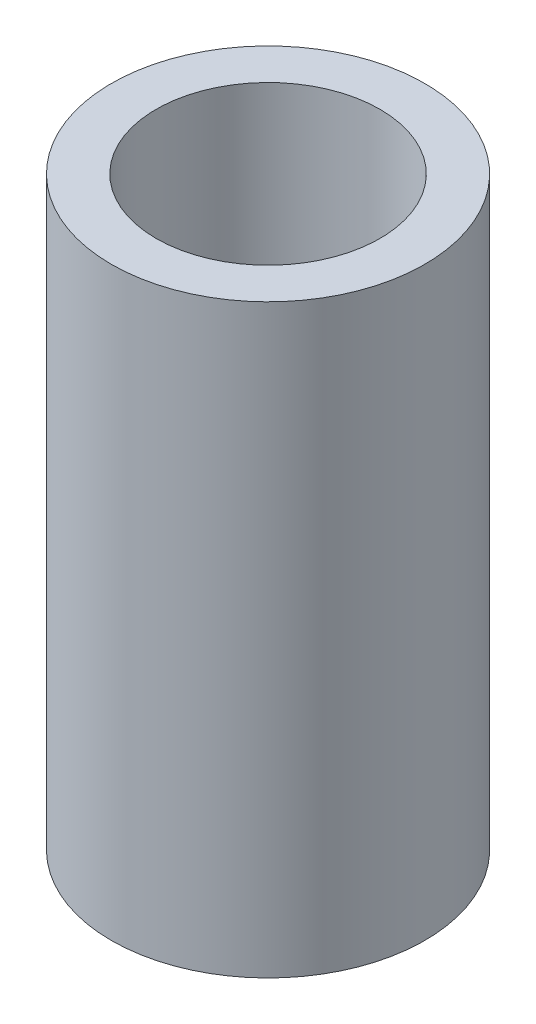
SolidWorks part; units mm, degrees
ref_plane "Front Plane" through (0, 0, 0) normal (0, 0, 1) x (1, 0, 0)
ref_plane "Top Plane" through (0, 0, 0) normal (0, 1, 0) x (1, 0, 0)
ref_plane "Right Plane" through (0, 0, 0) normal (1, 0, 0) x (0, 0, -1)
sketch "Sketch1" plane through (0, 0, 0) normal (0, 1, 0) x (1, 0, 0)
  circle A0 centre (0, 0) radius 1.5875
  circle A1 centre (0, 0) radius 2.2225
  dimension "D1" = 3.175
  dimension "D2" = 4.445
extrude "Boss-Extrude1" add sketch "Sketch1" along normal blind 8.3058
